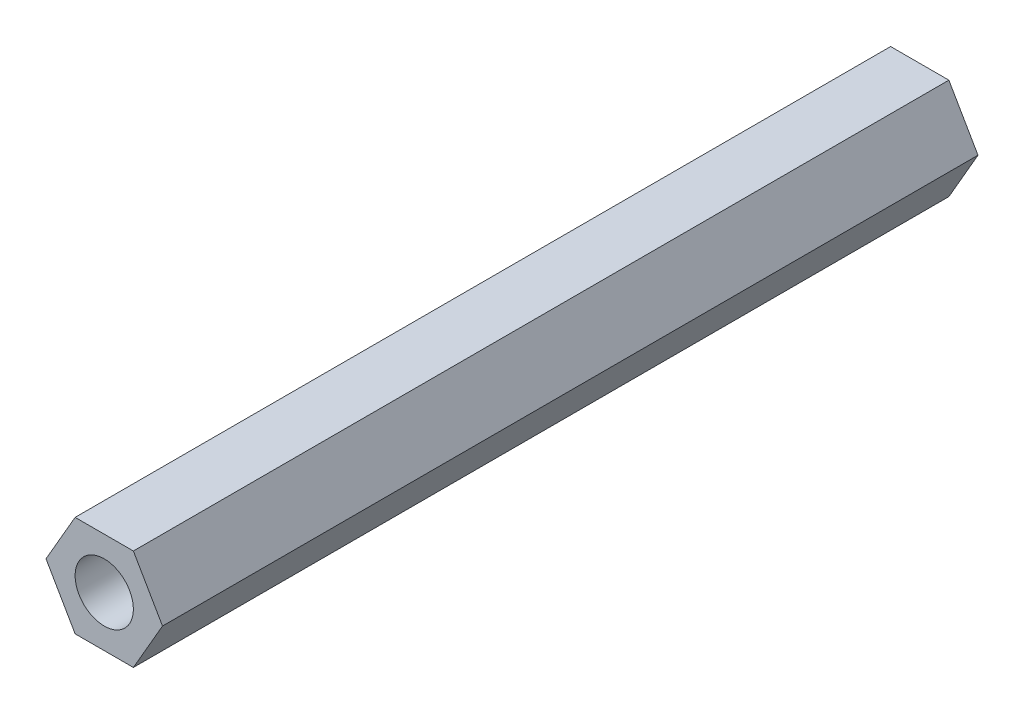
SolidWorks part; units mm, degrees
material "普通碳钢"
ref_plane "前视" through (0, 0, 0) normal (0, 0, 1) x (1, 0, 0)
ref_plane "上视" through (0, 0, 0) normal (0, 1, 0) x (1, 0, 0)
ref_plane "右视" through (0, 0, 0) normal (1, 0, 0) x (0, 0, -1)
sketch "草图1" plane through (0, 0, 0) normal (0, 0, 1) x (1, 0, 0)
  line L0 (0, 0) -> (2.5, 0)
  line L1 (2.5, 0) -> (3.75, -2.1651)
  line L2 (3.75, -2.1651) -> (2.5, -4.3301)
  line L3 (2.5, -4.3301) -> (0, -4.3301)
  line L4 (0, -4.3301) -> (-1.25, -2.1651)
  line L5 (-1.25, -2.1651) -> (0, 0)
  dimension "D1" = 5
  dimension "D2" = 5
extrude "凸台-拉伸1" add sketch "草图1" along normal blind 35
hole_wizard "M3 螺纹孔1" positions "草图3" profile "草图2" tap size "M3" standard "GB" end condition through all
sketch "草图3" plane through (0, 0, 35) normal (0, 0, 1) x (1, 0, 0)
  line L0 (-1.25, -2.1651) -> (3.75, -2.1651) construction
  line L2 (1.25, 0) -> (1.25, -4.3301) construction
  line L3 (2.5, 0) -> (0, 0) construction
  line L4 (0, -4.3301) -> (2.5, -4.3301) construction
  point P0 (1.25, -2.1651)
cosmetic thread "孔螺蚊线1" parameters "D2"=3
sketch "草图2" plane through (1.25, -2.1651, 35) normal (1, 0, 0) x (0, -1, 0)
  line L0 (0, 0) -> (0, 35)
  line L1 (0, 35) -> (1.25, 35)
  line L2 (1.25, 35) -> (1.25, 0)
  line L5 (1.25, 0) -> (0, 0)
  line L11 (0, -6.35) -> (0, 107.95) construction
  dimension "通孔螺纹孔钻头直径" = 2.5
  dimension "通孔螺纹孔钻头深度" = 35
